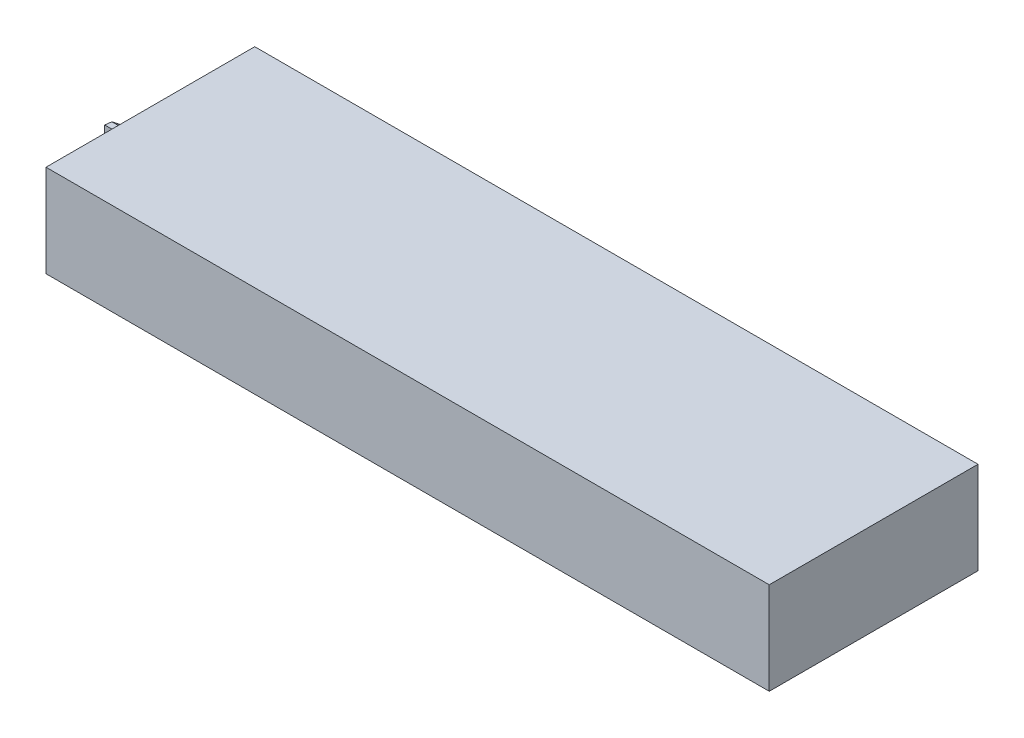
SolidWorks part; units mm, degrees
material "A-2 Steel"
ref_plane "Alzado" through (0, 0, 0) normal (0, 0, 1) x (1, 0, 0)
ref_plane "Planta" through (0, 0, 0) normal (0, 1, 0) x (1, 0, 0)
ref_plane "Vista lateral" through (0, 0, 0) normal (1, 0, 0) x (0, 0, -1)
sketch "Croquis1" plane through (0, 0, 0) normal (0, 1, 0) x (1, 0, 0)
  line L1 (11, 3.175) -> (-11, 3.175)
  line L2 (11, 3.175) -> (11, -3.175)
  line L3 (11, -3.175) -> (-11, -3.175)
  line L4 (-11, 3.175) -> (-11, -3.175)
  line L5 (0, -3.175) -> (0, 3.175) construction
  line L6 (11, 0) -> (-11, 0) construction
  point P124 (0, 0)
  dimension "D1" = 6.35
  dimension "D2" = 22
extrude "Saliente-Extruir1" add sketch "Croquis1" along normal blind 2.8067
sketch "Croquis2" plane through (-11, 0, 0) normal (-1, 0, 0) x (0, 0, 1)
  line L0 (1.35, 2.8067) -> (1.35, -0.1549) construction
  line L1 (-3.175, 2.8067) -> (3.175, 2.8067) construction
  line L2 (-3.175, 0) -> (3.175, 0) construction
  line L3 (-1.35, 2.8067) -> (-1.35, -0.1549) construction
  line L4 (-1.35, 1.3259) -> (1.35, 1.3259) construction
  line L5 (0, 0) -> (0, 1.3259) construction
  text T0 "4" font "Arial" height 2.7
  dimension "D1" = 2.7
  dimension "D2" = 0.1549
extrude "Saliente-Extruir2" add sketch "Croquis2" along normal up to surface (0.8293 mm away)
sketch "Croquis5" plane through (-11, 0, 0) normal (-1, 0, 0) x (0, 0, 1)
  line L0 (1.2357, 0.9209) -> (1.2357, 1.0385)
  line L1 (1.2357, 1.0385) -> (0.578, 1.0385)
  line L2 (0.578, 1.0385) -> (0.578, 2.2154)
  line L3 (-0.6263, 1.1528) -> (0.3462, 1.1528)
  line L4 (0.3462, 1.1528) -> (0.3462, 1.9024)
  line L5 (0.3462, 1.9024) -> (-0.6263, 1.1528)
  line L6 (-0.6263, 1.1528) -> (0.3462, 1.1528)
  line L7 (0.3462, 1.1528) -> (0.3462, 1.9024)
  line L8 (0.3462, 1.9024) -> (-0.6263, 1.1528)
  line L9 (0.578, 2.2154) -> (0.3851, 2.2154)
  line L10 (0.3851, 2.2154) -> (-1.2011, 0.9927)
  line L11 (1.35, 0.8066) -> (1.35, 1.1528)
  line L12 (1.35, 1.1528) -> (0.6923, 1.1528)
  line L13 (0.6923, 1.1528) -> (0.6923, 2.3297)
  line L14 (0.6923, 2.3297) -> (0.3462, 2.3297)
  line L15 (0.3462, 2.3297) -> (-1.3154, 1.049)
  line L16 (-1.3154, 1.049) -> (-1.3154, 0.8066)
  line L17 (-1.3154, 0.8066) -> (0.3462, 0.8066)
  line L18 (0.3462, 0.8066) -> (0.3462, 0.4605)
  line L19 (0.3462, 0.4605) -> (0.6923, 0.4605)
  line L20 (0.6923, 0.4605) -> (0.6923, 0.8066)
  line L21 (0.6923, 0.8066) -> (1.35, 0.8066)
  line L22 (1.35, 0.8066) -> (1.35, 1.1528)
  line L23 (1.35, 1.1528) -> (0.6923, 1.1528)
  line L24 (0.6923, 1.1528) -> (0.6923, 2.3297)
  line L25 (0.6923, 2.3297) -> (0.3462, 2.3297)
  line L26 (0.3462, 2.3297) -> (-1.3154, 1.049)
  line L27 (-1.3154, 1.049) -> (-1.3154, 0.8066)
  line L28 (-1.3154, 0.8066) -> (0.3462, 0.8066)
  line L29 (0.3462, 0.8066) -> (0.3462, 0.4605)
  line L30 (0.3462, 0.4605) -> (0.6923, 0.4605)
  line L31 (0.6923, 0.4605) -> (0.6923, 0.8066)
  line L32 (0.6923, 0.8066) -> (1.35, 0.8066)
  line L33 (-1.2011, 0.9927) -> (-1.2011, 0.9209)
  line L34 (-1.2011, 0.9209) -> (0.4605, 0.9209)
  line L35 (0.4605, 0.9209) -> (0.4605, 0.5748)
  line L36 (0.4605, 0.5748) -> (0.578, 0.5748)
  line L37 (0.578, 0.5748) -> (0.578, 0.9209)
  line L38 (0.578, 0.9209) -> (1.2357, 0.9209)
  line L39 (0.4605, 1.0385) -> (0.4605, 2.1349)
  line L40 (0.4605, 2.1349) -> (-0.9618, 1.0385)
  line L41 (-0.9618, 1.0385) -> (0.4605, 1.0385)
  line M40 (1.35, 1.1528) -> (1.35, 0.8066)
  line M41 (1.35, 0.8066) -> (0.6923, 0.8066)
  line M42 (0.6923, 0.8066) -> (0.6923, 0.4605)
  line M43 (0.6923, 0.4605) -> (0.3462, 0.4605)
  line M44 (0.3462, 0.4605) -> (0.3462, 0.8066)
  line M45 (0.3462, 0.8066) -> (-1.3154, 0.8066)
  line M46 (-1.3154, 0.8066) -> (-1.3154, 1.049)
  line M47 (-1.3154, 1.049) -> (0.3462, 2.3297)
  line M48 (0.3462, 2.3297) -> (0.6923, 2.3297)
  line M49 (0.6923, 2.3297) -> (0.6923, 1.1528)
  line M50 (0.6923, 1.1528) -> (1.35, 1.1528)
  dimension "D1" = 0
  dimension "D2" = 0
  dimension "D3" = 0.1143
  dimension "D4" = 0.1143
extrude "Cortar-Extruir1" cut sketch "Croquis5" along normal through all contours L38 L37 L36 L35 L34 L33 L10 L9 L2 L1 L0 M40 M50 M49 M48 M47 M46 M45 M44 M43 M42 M41 | L40 L41 L39 L8 L7 L6
sketch3d "Croquis3D4"
  line L0 (-11.7952, 2.1349, 0.4605) -> (-11.7952, 1.0385, 0.4605) construction
  line L1 (-11.7952, 2.1349, 0.4605) -> (-11.7952, 1.0385, 0.4605)
  line L5 (-11.966, 0.9209, 1.2357) -> (-11.966, 1.0385, 1.2357)
  line L6 (-11.8107, 1.0385, 0.578) -> (-11.8107, 2.2154, 0.578)
  line L7 (-11.9548, 0.9927, -1.2011) -> (-11.9548, 0.9209, -1.2011)
  line L8 (-11.7952, 0.9209, 0.4605) -> (-11.7952, 0.5748, 0.4605)
  line L9 (-11.8107, 0.5748, 0.578) -> (-11.8107, 0.9209, 0.578)
  line L10 (-11.966, 0.9209, 1.2357) -> (-11.966, 1.0385, 1.2357)
  line L11 (-11.8107, 1.0385, 0.578) -> (-11.8107, 2.2154, 0.578)
  line L12 (-11.9548, 0.9927, -1.2011) -> (-11.9548, 0.9209, -1.2011)
  line L13 (-11.7952, 0.9209, 0.4605) -> (-11.7952, 0.5748, 0.4605)
  line L14 (-11.8107, 0.5748, 0.578) -> (-11.8107, 0.9209, 0.578)
  arc A0 (-11.7952, 1.0385, 0.4605) -> (-11.8869, 1.0385, -0.9618) centre (-15.7307, 1.0385, 0) ccw construction
  arc A1 (-11.7952, 1.0385, 0.4605) -> (-11.8869, 1.0385, -0.9618) centre (-15.7307, 1.0385, 0) ccw
  arc A5 (-11.8107, 0.9209, 0.578) -> (-11.966, 0.9209, 1.2357) centre (-15.7307, 0.9209, 0) ccw
  arc A6 (-11.966, 1.0385, 1.2357) -> (-11.8107, 1.0385, 0.578) centre (-15.7307, 1.0385, 0) ccw
  arc A7 (-11.8107, 2.2154, 0.578) -> (-11.7871, 2.2154, 0.3851) centre (-15.7307, 2.2154, 0) ccw
  arc A8 (-11.9548, 0.9209, -1.2011) -> (-11.7952, 0.9209, 0.4605) centre (-15.7307, 0.9209, 0) ccw
  arc A9 (-11.7952, 0.5748, 0.4605) -> (-11.8107, 0.5748, 0.578) centre (-15.7307, 0.5748, 0) ccw
  arc A10 (-11.8107, 0.9209, 0.578) -> (-11.966, 0.9209, 1.2357) centre (-15.7307, 0.9209, 0) ccw
  arc A11 (-11.966, 1.0385, 1.2357) -> (-11.8107, 1.0385, 0.578) centre (-15.7307, 1.0385, 0) ccw
  arc A12 (-11.8107, 2.2154, 0.578) -> (-11.7871, 2.2154, 0.3851) centre (-15.7307, 2.2154, 0) ccw
  arc A13 (-11.9548, 0.9209, -1.2011) -> (-11.7952, 0.9209, 0.4605) centre (-15.7307, 0.9209, 0) ccw
  arc A14 (-11.7952, 0.5748, 0.4605) -> (-11.8107, 0.5748, 0.578) centre (-15.7307, 0.5748, 0) ccw
  spline S0 degree 3 poles (-11.8869, 1.0385, -0.9618) (-11.7703, 1.3977, -0.4959) (-11.7394, 1.7671, -0.0166) (-11.7952, 2.1349, 0.4605) knots 0 0 0 0 1 1 1 1 weights 1 0.98913 0.98913 1 construction
  spline S1 degree 3 poles (-11.7871, 2.2154, 0.3851) (-11.7347, 1.8019, -0.1514) (-11.7914, 1.3887, -0.6874) (-11.9548, 0.9927, -1.2011) knots 0 0 0 0 1 1 1 1 weights 1 0.986357 0.986357 1
  spline S2 degree 3 poles (-11.7871, 2.2154, 0.3851) (-11.7347, 1.8019, -0.1514) (-11.7914, 1.3887, -0.6874) (-11.9548, 0.9927, -1.2011) knots 0 0 0 0 1 1 1 1 weights 1 0.986357 0.986357 1
  spline S3 degree 3 poles (-11.8869, 1.0385, -0.9618) (-11.7703, 1.3977, -0.4959) (-11.7394, 1.7671, -0.0166) (-11.7952, 2.1349, 0.4605) knots 0 0 0 0 1 1 1 1 weights 1 0.98913 0.98913 1
  point P8 (-15.7307, -3.0415, 0)
  point P9 (-15.7307, 5.0009, 0)
  point P12 (-15.7307, 5.0009, 0)
  point P14 (-15.7307, 5.0009, 0)
  point P18 (-15.7307, 6.1778, 0)
  point P24 (-15.7307, -3.0415, 0)
  point P30 (-15.7307, -3.3876, 0)
  point P31 (-15.7307, -3.0415, 0)
  point P32 (-15.7307, 5.0009, 0)
  point P33 (-15.7307, 6.1778, 0)
  point P34 (-15.7307, -3.0415, 0)
  point P35 (-15.7307, -3.3876, 0)
  dimension "D1" = 0
sketch "Croquis3" plane through (-11, 0, 0) normal (-1, 0, 0) x (0, 0, 1)
  line L0 (1.0892, 1.5497) -> (1.0892, 2.841)
  line L1 (-1.7123, 1.2434) -> (-1.7123, 0.4098)
  line L2 (-0.0507, 0.4098) -> (-0.0507, 0.0636)
  line L3 (1.0892, 0.0636) -> (1.0892, 0.4098)
  line L4 (1.7469, 0.4098) -> (1.7469, 1.5497)
  line L5 (0.578, 0.9209) -> (1.2357, 0.9209)
  line L6 (0.578, 0.9209) -> (1.2357, 0.9209)
  line L7 (1.2357, 0.9209) -> (1.2357, 1.0385)
  line L8 (1.2357, 0.9209) -> (1.2357, 1.0385)
  line L9 (1.2357, 1.0385) -> (0.578, 1.0385)
  line L18 (0.4605, 2.1349) -> (-0.9618, 1.0385)
  line L19 (0.4605, 2.1349) -> (-0.9618, 1.0385)
  line L20 (-0.9618, 1.0385) -> (0.4605, 1.0385)
  line L24 (-0.9618, 1.0385) -> (0.4605, 1.0385)
  line L25 (0.4605, 1.0385) -> (0.4605, 2.1349)
  line L26 (0.4605, 1.0385) -> (0.4605, 2.1349)
  line L32 (1.2357, 1.0385) -> (0.578, 1.0385)
  line L33 (0.578, 1.0385) -> (0.578, 2.2154)
  line L34 (0.578, 1.0385) -> (0.578, 2.2154)
  line L35 (0.578, 2.2154) -> (0.3851, 2.2154)
  line L36 (0.578, 2.2154) -> (0.3851, 2.2154)
  line L37 (0.3851, 2.2154) -> (-1.2011, 0.9927)
  line L38 (0.3851, 2.2154) -> (-1.2011, 0.9927)
  line L39 (-1.2011, 0.9927) -> (-1.2011, 0.9209)
  line L40 (-1.2011, 0.9927) -> (-1.2011, 0.9209)
  line L41 (-1.2011, 0.9209) -> (0.4605, 0.9209)
  line L42 (-1.2011, 0.9209) -> (0.4605, 0.9209)
  line L43 (0.4605, 0.9209) -> (0.4605, 0.5748)
  line L44 (0.4605, 0.9209) -> (0.4605, 0.5748)
  line L45 (0.4605, 0.5748) -> (0.578, 0.5748)
  line L46 (0.4605, 0.5748) -> (0.578, 0.5748)
  line L47 (0.578, 0.5748) -> (0.578, 0.9209)
  line L48 (0.578, 0.5748) -> (0.578, 0.9209)
  spline S6 degree 3 poles (1.0892, 2.841) (0.9979, 2.8187) (0.816, 2.7736) (0.5396, 2.7036) (0.262, 2.6318) (0.0758, 2.5826) (-0.017, 2.5578) knots 1.317562 1.317562 1.317562 1.317562 1.365718 1.413874 1.46203 1.510186 1.510186 1.510186 1.510186
  spline S7 degree 3 poles (-0.017, 2.5578) (-0.1607, 2.4509) (-0.4459, 2.2364) (-0.8768, 1.9057) (-1.3026, 1.5721) (-1.5754, 1.3541) (-1.7123, 1.2434) knots -1.757163 -1.757163 -1.757163 -1.757163 -1.63912 -1.521076 -1.403032 -1.284989 -1.284989 -1.284989 -1.284989
  spline S8 degree 3 poles (-1.7123, 0.4098) (-1.5789, 0.4065) (-1.3155, 0.4018) (-0.8999, 0.3993) (-0.4777, 0.4018) (-0.1927, 0.4066) (-0.0507, 0.4098) knots 1.157021 1.157021 1.157021 1.157021 1.262493 1.367966 1.473438 1.57891 1.57891 1.57891 1.57891
  spline S9 degree 3 poles (-0.0507, 0.0636) (0.0452, 0.0624) (0.2373, 0.0605) (0.5239, 0.0596) (0.8089, 0.0605) (0.9955, 0.0624) (1.0892, 0.0636) knots 1.57891 1.57891 1.57891 1.57891 1.64019 1.70147 1.76275 1.824031 1.824031 1.824031 1.824031
  spline S10 degree 3 poles (1.0892, 0.4098) (1.1451, 0.4092) (1.2575, 0.4084) (1.423, 0.408) (1.5868, 0.4084) (1.6933, 0.4092) (1.7469, 0.4098) knots 1.824031 1.824031 1.824031 1.824031 1.866445 1.90886 1.951274 1.993689 1.993689 1.993689 1.993689
  spline S11 degree 3 poles (1.7469, 1.5497) (1.6933, 1.5502) (1.5868, 1.551) (1.423, 1.5515) (1.2575, 1.5511) (1.1451, 1.5502) (1.0892, 1.5497) knots 1.147904 1.147904 1.147904 1.147904 1.190318 1.232733 1.275148 1.317562 1.317562 1.317562 1.317562
  dimension "D1" = 0
  dimension "D3" = 0
sketch3d "Croquis3D1"
  line L0 (-11.7835, 1.9024, 0.3462) -> (-11.7835, 1.1528, 0.3462) construction
  line L1 (-11.7835, 1.9024, 0.3462) -> (-11.7835, 1.1528, 0.3462)
  line L5 (-11.966, 1.0385, 1.2357) -> (-11.966, 0.9209, 1.2357)
  line L6 (-11.966, 1.0385, 1.2357) -> (-11.966, 0.9209, 1.2357)
  line L7 (-11.8107, 2.2154, 0.578) -> (-11.8107, 1.0385, 0.578)
  line L8 (-11.8107, 2.2154, 0.578) -> (-11.8107, 1.0385, 0.578)
  line L9 (-11.9548, 0.9209, -1.2011) -> (-11.9548, 0.9927, -1.2011)
  line L23 (-11.9548, 0.9209, -1.2011) -> (-11.9548, 0.9927, -1.2011)
  line L24 (-11.7952, 0.5748, 0.4605) -> (-11.7952, 0.9209, 0.4605)
  line L25 (-11.7952, 0.5748, 0.4605) -> (-11.7952, 0.9209, 0.4605)
  line L26 (-11.8107, 0.9209, 0.578) -> (-11.8107, 0.5748, 0.578)
  line L27 (-11.8107, 0.9209, 0.578) -> (-11.8107, 0.5748, 0.578)
  arc A0 (-11.966, 0.9209, 1.2357) -> (-11.8107, 0.9209, 0.578) centre (-15.7307, 0.9209, 0) ccw
  arc A1 (-11.966, 0.9209, 1.2357) -> (-11.8107, 0.9209, 0.578) centre (-15.7307, 0.9209, 0) ccw
  arc A2 (-11.8107, 1.0385, 0.578) -> (-11.966, 1.0385, 1.2357) centre (-15.7307, 1.0385, 0) ccw
  arc A3 (-11.8107, 1.0385, 0.578) -> (-11.966, 1.0385, 1.2357) centre (-15.7307, 1.0385, 0) ccw
  arc A13 (-11.7871, 2.2154, 0.3851) -> (-11.8107, 2.2154, 0.578) centre (-15.7307, 2.2154, 0) ccw
  arc A14 (-11.7871, 2.2154, 0.3851) -> (-11.8107, 2.2154, 0.578) centre (-15.7307, 2.2154, 0) ccw
  arc A15 (-11.7952, 0.9209, 0.4605) -> (-11.9548, 0.9209, -1.2011) centre (-15.7307, 0.9209, 0) ccw
  arc A16 (-11.7952, 0.9209, 0.4605) -> (-11.9548, 0.9209, -1.2011) centre (-15.7307, 0.9209, 0) ccw
  arc A17 (-11.8107, 0.5748, 0.578) -> (-11.7952, 0.5748, 0.4605) centre (-15.7307, 0.5748, 0) ccw
  arc A18 (-11.8107, 0.5748, 0.578) -> (-11.7952, 0.5748, 0.4605) centre (-15.7307, 0.5748, 0) ccw
  spline S0 degree 3 poles (-11.8182, 1.1528, -0.6263) (-11.7666, 1.401, -0.3044) (-11.755, 1.6521, 0.0214) (-11.7835, 1.9024, 0.3462) knots 0 0 0 0 1 1 1 1 weights 1 0.994955 0.994955 1 construction
  spline S1 degree 3 poles (-11.7835, 1.1528, 0.3462) (-11.755, 1.1528, 0.0214) (-11.7666, 1.1528, -0.3044) (-11.8182, 1.1528, -0.6263) knots 0 0 0 0 1 1 1 1 weights 1 0.994955 0.994955 1 construction
  spline S2 degree 3 poles (-11.8182, 1.1528, -0.6263) (-11.7666, 1.401, -0.3044) (-11.755, 1.6521, 0.0214) (-11.7835, 1.9024, 0.3462) knots 0 0 0 0 1 1 1 1 weights 1 0.994955 0.994955 1
  spline S3 degree 3 poles (-11.7835, 1.1528, 0.3462) (-11.755, 1.1528, 0.0214) (-11.7666, 1.1528, -0.3044) (-11.8182, 1.1528, -0.6263) knots 0 0 0 0 1 1 1 1 weights 1 0.994955 0.994955 1
  spline S5 degree 3 poles (-11.9548, 0.9927, -1.2011) (-11.7914, 1.3887, -0.6874) (-11.7347, 1.8019, -0.1514) (-11.7871, 2.2154, 0.3851) knots 0 0 0 0 1 1 1 1 weights 1 0.986357 0.986357 1
  spline S6 degree 3 poles (-11.9548, 0.9927, -1.2011) (-11.7914, 1.3887, -0.6874) (-11.7347, 1.8019, -0.1514) (-11.7871, 2.2154, 0.3851) knots 0 0 0 0 1 1 1 1 weights 1 0.986357 0.986357 1
  point P1 (-15.7307, 4.8833, 0)
  point P2 (-15.7307, 4.8833, 0)
  point P4 (-15.7307, -2.9239, 0)
  point P5 (-15.7307, -2.9239, 0)
  point P7 (-15.7307, -1.747, 0)
  point P8 (-15.7307, -1.747, 0)
  point P10 (-15.7307, 4.8833, 0)
  point P11 (-15.7307, 4.8833, 0)
  point P13 (-15.7307, 4.5372, 0)
  point P14 (-15.7307, 4.5372, 0)
  dimension "D1" = 0
